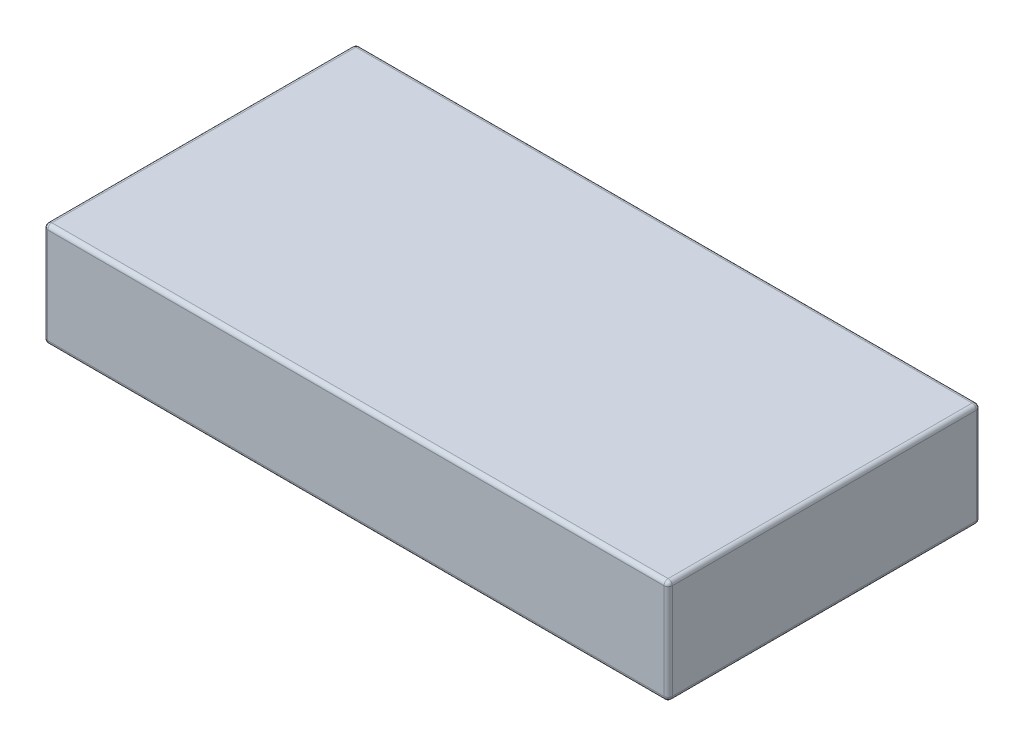
SolidWorks part; units mm, degrees
ref_plane "前视基准面" through (0, 0, 0) normal (0, 0, 1) x (1, 0, 0)
ref_plane "上视基准面" through (0, 0, 0) normal (0, 1, 0) x (1, 0, 0)
ref_plane "右视基准面" through (0, 0, 0) normal (1, 0, 0) x (0, 0, -1)
sketch "草图1" plane through (0, 0, 0) normal (0, 1, 0) x (1, 0, 0)
  line L1 (-15, -7.5) -> (15, -7.5)
  line L2 (-15, -7.5) -> (-15, 7.5)
  line L3 (-15, 7.5) -> (15, 7.5)
  line L4 (15, -7.5) -> (15, 7.5)
extrude "凸台-拉伸1" add sketch "草图1" along normal blind 5
sketch "草图2" plane through (-15, 0, 0) normal (-1, 0, 0) x (0, 0, 1)
  line L0 (-1.5, 0) -> (-1.5, 0.6771)
  line L1 (-7.5, 0) -> (7.5, 0) construction
  line L2 (-1.5, 0) -> (1.5, 0)
  line L3 (1.5, 0) -> (1.5, 0.6771)
  line L4 (-1.95, 2.8) -> (1.95, 2.8)
  line L5 (-1.95, 2.8) -> (-1.95, 1.5556)
  line L6 (1.95, 2.8) -> (1.95, 1.5556)
  arc A0 (-1.95, 1.5556) -> (-1.5, 0.6771) centre (0, 2) ccw
  arc A1 (1.5, 0.6771) -> (1.95, 1.5556) centre (0, 2) ccw
extrude "切除-拉伸1" cut sketch "草图2" against normal blind 24.45
fillet "圆角1" radius 0.2 16 edges at (15, 2.5, -7.5) (-15, 2.5, -7.5) (-15, 0, 4.5) (15, 0, 0) (0, 0, -7.5) (-15, 0, -4.5) (-2.775, 0, -1.5) (9.45, 0, 0) (-2.775, 0, 1.5) (-15, 2.5, 7.5) (15, 2.5, 7.5) (0, 0, 7.5) (0, 5, -7.5) (15, 5, 0) (0, 5, 7.5) (-15, 5, 0)
